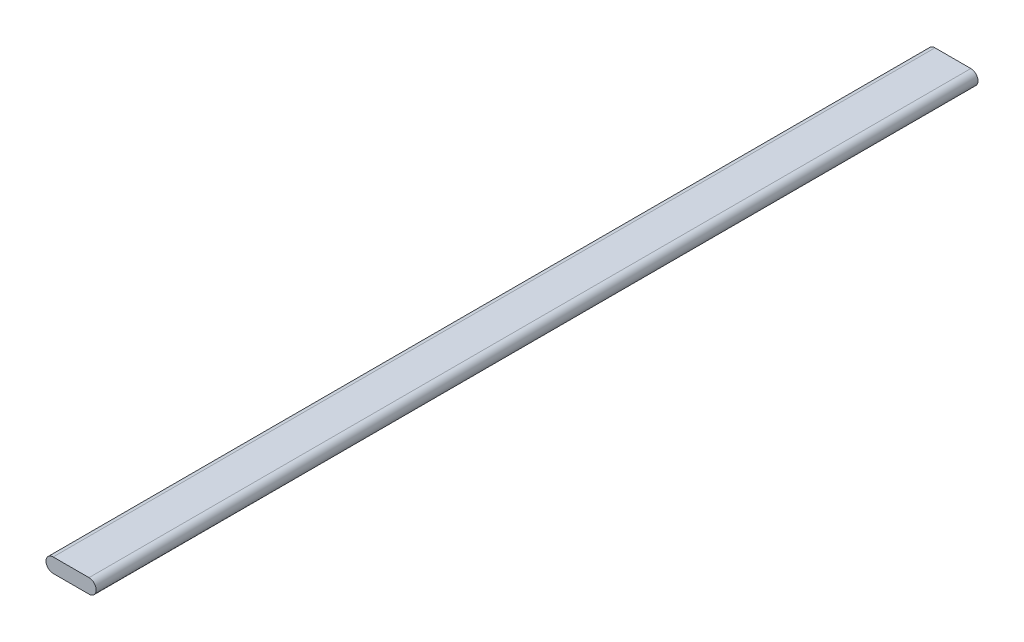
SolidWorks part; units mm, degrees
material "1023 Carbon Steel Sheet (SS)"
ref_plane "Ön Düzlem" through (0, 0, 0) normal (0, 0, 1) x (1, 0, 0)
ref_plane "Üst Düzlem" through (0, 0, 0) normal (0, 1, 0) x (1, 0, 0)
ref_plane "Sağ Düzlem" through (0, 0, 0) normal (1, 0, 0) x (0, 0, -1)
sketch "Sketch1" plane through (0, 0, 0) normal (0, 0, 1) x (1, 0, 0)
  line L0 (-12.5, 0) -> (12.5, 0) construction
  line L1 (-12.5, 5) -> (12.5, 5)
  line L2 (-12.5, -5) -> (12.5, -5)
  arc A0 (-12.5, 5) -> (-12.5, -5) centre (-12.5, 0) ccw
  arc A1 (12.5, -5) -> (12.5, 5) centre (12.5, 0) ccw
  point P3 (0, 0)
  point P8 (0, 0)
  dimension "D2" = 5
  dimension "D1" = 25
extrude "Boss-Extrude1" add sketch "Sketch1" against normal blind 615
sketch "Sketch2" plane through (0, -5, 0) normal (0, -1, 0) x (1, 0, 0)
  line L0 (-12.5, -615) -> (-12.5, 0) construction
  line L1 (-12.5, -615) -> (12.5, -615) construction
  circle A0 centre (0, -15) radius 4
  circle A1 centre (0, -600) radius 4
  point P5 (0, 0)
  dimension "D1" = 8
  dimension "D4" = 8
  dimension "D2" = 15
  dimension "D3" = 12.5
  dimension "D5" = 12.5
  dimension "D6" = 15
extrude "Cut-Extrude1" cut sketch "Sketch2" against normal blind 5
